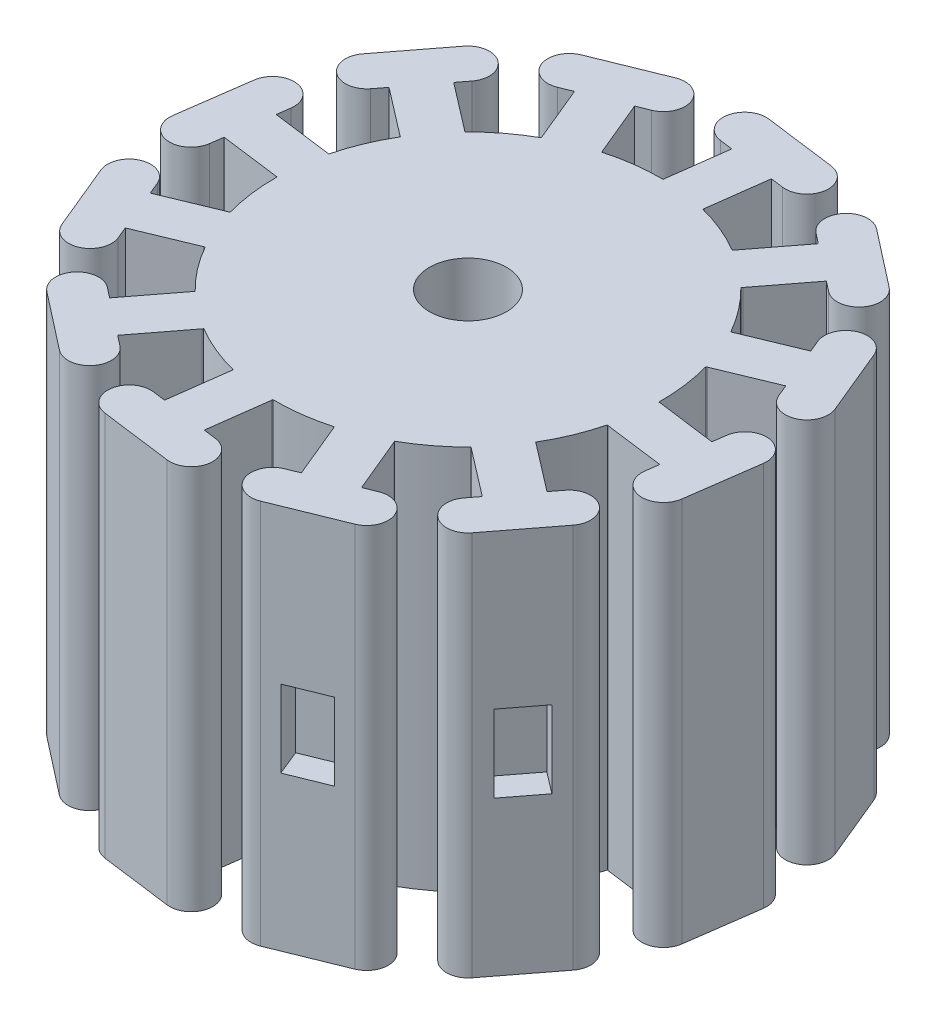
SolidWorks part; units mm, degrees
ref_plane "前视基准面" through (0, 0, 0) normal (0, 0, 1) x (1, 0, 0)
ref_plane "上视基准面" through (0, 0, 0) normal (0, 1, 0) x (1, 0, 0)
ref_plane "右视基准面" through (0, 0, 0) normal (1, 0, 0) x (0, 0, -1)
other "Configuration Table"
sketch "草图1" plane through (0, 0, 0) normal (0, 1, 0) x (1, 0, 0)
  line L0 (-16.5172, 2.1608) -> (-12.6081, 1.6494)
  line L25 (-16.1892, 4.5192) -> (-16.8451, -0.1975)
  line L26 (-19.002, 4.9103) -> (-19.6579, 0.1936)
  line L27 (-15.3899, -6.3747) -> (-11.7476, -4.866)
  line L28 (-16.3011, -4.1749) -> (-14.4787, -8.5745)
  line L29 (-18.9211, -5.2705) -> (-17.106, -9.6524)
  line L30 (-13.2156, 10.1407) -> (-10.0879, 7.7407)
  line L31 (-12.0083, -11.7607) -> (-8.2515, -14.6871)
  line L32 (-13.7535, -14.0011) -> (-9.9966, -16.9274)
  line L33 (-6.3873, 15.3847) -> (-4.8756, 11.7437)
  line L34 (-4.535, -16.2046) -> (0.1864, -16.8262)
  line L35 (-4.8962, -19.0214) -> (-0.1938, -19.6405)
  line L36 (2.1743, 16.5154) -> (1.6597, 12.6068)
  line L37 (4.1809, -16.2799) -> (8.5936, -14.4896)
  line L38 (5.2485, -18.9114) -> (9.6613, -17.1211)
  line L39 (10.1299, 13.2239) -> (7.7325, 10.0942)
  line L40 (11.7661, -12.0297) -> (14.6651, -8.2517)
  line L41 (14.0249, -13.7509) -> (16.9123, -9.988)
  line L42 (15.3899, 6.3747) -> (11.7476, 4.866)
  line L43 (16.1892, -4.5192) -> (16.8451, 0.1975)
  line L44 (19.002, -4.9103) -> (19.6579, -0.1936)
  line L45 (16.5172, -2.1608) -> (12.6081, -1.6494)
  line L46 (16.3011, 4.1749) -> (14.4787, 8.5745)
  line L47 (18.9211, 5.2705) -> (17.106, 9.6524)
  line L48 (13.2156, -10.1407) -> (10.0879, -7.7407)
  line L49 (12.0083, 11.7607) -> (8.2515, 14.6871)
  line L50 (13.7535, 14.0011) -> (9.9966, 16.9274)
  line L51 (6.3873, -15.3847) -> (4.8756, -11.7437)
  line L52 (4.535, 16.2046) -> (-0.1864, 16.8262)
  line L53 (4.9056, 19.0202) -> (0.1843, 19.6417)
  line L54 (-2.1743, -16.5154) -> (-1.6597, -12.6068)
  line L55 (-4.1809, 16.2799) -> (-8.5936, 14.4896)
  line L56 (-5.2485, 18.9114) -> (-9.6613, 17.1211)
  line L57 (-10.1299, -13.2239) -> (-7.7325, -10.0942)
  line L58 (-11.7661, 12.0297) -> (-14.6651, 8.2517)
  line L59 (-14.0249, 13.7509) -> (-16.9123, 9.988)
  line L60 (-6.3873, 15.3847) -> (-4.8756, 11.7437) construction
  line L61 (-4.9828, 15.9678) -> (-3.4711, 12.3268)
  line L62 (-7.7918, 14.8016) -> (-6.2801, 11.1606)
  line L63 (2.1743, 16.5154) -> (1.6597, 12.6068) construction
  line L64 (3.682, 16.3169) -> (3.1674, 12.4083)
  line L65 (0.6666, 16.7139) -> (0.152, 12.8053)
  line L66 (10.1299, 13.2239) -> (7.7325, 10.0942) construction
  line L67 (11.3371, 12.2991) -> (8.9397, 9.1695)
  line L68 (8.9227, 14.1487) -> (6.5253, 11.019)
  line L69 (15.3899, 6.3747) -> (11.7476, 4.866) construction
  line L70 (15.9719, 4.9697) -> (12.3296, 3.4611)
  line L71 (14.808, 7.7797) -> (11.1657, 6.271)
  line L72 (12.6081, -1.6494) -> (16.5172, -2.1608) construction
  line L73 (12.8054, -0.1415) -> (16.7145, -0.6529)
  line L74 (12.4109, -3.1573) -> (16.3199, -3.6687)
  line L75 (10.0879, -7.7407) -> (13.2156, -10.1407) construction
  line L76 (11.0137, -6.5343) -> (14.1414, -8.9342)
  line L77 (9.1622, -8.9472) -> (12.2899, -11.3472)
  line L78 (4.8756, -11.7437) -> (6.3873, -15.3847) construction
  line L79 (6.2801, -11.1606) -> (7.7918, -14.8016)
  line L80 (3.4711, -12.3268) -> (4.9828, -15.9678)
  line L81 (-1.6597, -12.6068) -> (-2.1743, -16.5154) construction
  line L82 (-0.152, -12.8053) -> (-0.6666, -16.7139)
  line L83 (-3.1674, -12.4083) -> (-3.682, -16.3169)
  line L84 (-7.7325, -10.0942) -> (-10.1299, -13.2239) construction
  line L85 (-6.5253, -11.019) -> (-8.9227, -14.1487)
  line L86 (-8.9397, -9.1695) -> (-11.3371, -12.2991)
  line L87 (-15.3899, -6.3747) -> (-11.7476, -4.866) construction
  line L88 (-15.9719, -4.9697) -> (-12.3296, -3.4611)
  line L89 (-14.808, -7.7797) -> (-11.1657, -6.271)
  line L90 (-16.5172, 2.1608) -> (-12.6081, 1.6494) construction
  line L91 (-16.3199, 3.6687) -> (-12.4109, 3.1573)
  line L92 (-16.7145, 0.6529) -> (-12.8054, 0.1415)
  line L93 (-13.2156, 10.1407) -> (-10.0879, 7.7407) construction
  line L94 (-12.2899, 11.3472) -> (-9.1622, 8.9472)
  line L95 (-14.1414, 8.9342) -> (-11.0137, 6.5343)
  circle A0 centre (0, 0) radius 2.54
  arc A1 (-16.0154, 7.7224) -> (-16.7805, 5.8774) centre (0, 0) ccw
  arc A2 (-7.7197, -16.0167) -> (-5.864, -16.7852) centre (0, 0) ccw
  circle A5 centre (0, 0) radius 12.7156
  arc A6 (-16.1892, 4.5192) -> (-19.002, 4.9103) centre (-17.5956, 4.7147) ccw
  arc A7 (-19.6579, 0.1936) -> (-16.8451, -0.1975) centre (-18.2515, -0.002) ccw
  arc A8 (-16.3011, -4.1749) -> (-18.9211, -5.2705) centre (-17.6093, -4.7271) ccw
  arc A9 (-17.106, -9.6524) -> (-14.4787, -8.5745) centre (-15.7942, -9.1091) ccw
  arc A10 (-12.0083, -11.7607) -> (-13.7535, -14.0011) centre (-12.8809, -12.8809) ccw
  arc A11 (-9.9966, -16.9274) -> (-8.2515, -14.6871) centre (-9.1241, -15.8073) ccw
  arc A12 (-4.535, -16.2046) -> (-4.8962, -19.0214) centre (-4.7108, -17.6136) ccw
  arc A13 (-0.1938, -19.6405) -> (0.1864, -16.8262) centre (-0.0084, -18.2327) ccw
  arc A14 (4.1809, -16.2799) -> (5.2485, -18.9114) centre (4.7147, -17.5956) ccw
  arc A15 (9.6613, -17.1211) -> (8.5936, -14.4896) centre (9.1275, -15.8053) ccw
  arc A16 (11.7661, -12.0297) -> (14.0249, -13.7509) centre (12.8984, -12.8865) ccw
  arc A17 (16.9123, -9.988) -> (14.6651, -8.2517) centre (15.7858, -9.1236) ccw
  arc A18 (16.1892, -4.5192) -> (19.002, -4.9103) centre (17.5956, -4.7147) ccw
  arc A19 (19.6579, -0.1936) -> (16.8451, 0.1975) centre (18.2515, 0.002) ccw
  arc A20 (16.3011, 4.1749) -> (18.9211, 5.2705) centre (17.6093, 4.7271) ccw
  arc A21 (17.106, 9.6524) -> (14.4787, 8.5745) centre (15.7942, 9.1091) ccw
  arc A22 (12.0083, 11.7607) -> (13.7535, 14.0011) centre (12.8809, 12.8809) ccw
  arc A23 (9.9966, 16.9274) -> (8.2515, 14.6871) centre (9.1241, 15.8073) ccw
  arc A24 (4.535, 16.2046) -> (4.9056, 19.0202) centre (4.7203, 17.6124) ccw
  arc A25 (0.1843, 19.6417) -> (-0.1864, 16.8262) centre (-0.001, 18.234) ccw
  arc A26 (-4.1809, 16.2799) -> (-5.2485, 18.9114) centre (-4.7147, 17.5956) ccw
  arc A27 (-9.6613, 17.1211) -> (-8.5936, 14.4896) centre (-9.1275, 15.8053) ccw
  arc A28 (-11.7661, 12.0297) -> (-14.0249, 13.7509) centre (-12.8984, 12.8865) ccw
  arc A29 (-16.9123, 9.988) -> (-14.6651, 8.2517) centre (-15.7858, 9.1236) ccw
  arc A32 (-17.7307, -1.3229) -> (-17.4684, -3.3142) centre (0, 0) ccw
  arc A35 (16.0154, -7.7224) -> (16.7805, -5.8774) centre (0, 0) ccw
  arc A36 (-14.6955, -10.0085) -> (-13.4802, -11.5936) centre (0, 0) ccw
  arc A37 (-4.9828, 15.9678) -> (-7.7918, 14.8016) centre (-6.3873, 15.3847) ccw
  arc A38 (-10.011, 14.6938) -> (-11.6044, 13.471) centre (0, 0) ccw
  arc A39 (-6.2801, 11.1606) -> (-3.4711, 12.3268) centre (-4.8756, 11.7437) ccw
  arc A40 (3.682, 16.3169) -> (0.6666, 16.7139) centre (2.1743, 16.5154) ccw
  arc A41 (0.152, 12.8053) -> (3.1674, 12.4083) centre (1.6597, 12.6068) ccw
  arc A42 (14.6955, 10.0085) -> (-3.3003, 17.471) centre (0, 0) ccw
  arc A43 (17.7307, 1.3229) -> (17.4684, 3.3142) centre (0, 0) ccw
  arc A44 (10.011, -14.6938) -> (11.6044, -13.471) centre (0, 0) ccw
  arc A45 (1.3199, -17.7309) -> (3.3003, -17.471) centre (0, 0) ccw
  arc A46 (11.3371, 12.2991) -> (8.9227, 14.1487) centre (10.1299, 13.2239) ccw
  arc A47 (6.5253, 11.019) -> (8.9397, 9.1695) centre (7.7325, 10.0942) ccw
  arc A48 (15.9719, 4.9697) -> (14.808, 7.7797) centre (15.3899, 6.3747) ccw
  arc A49 (11.1657, 6.271) -> (12.3296, 3.4611) centre (11.7476, 4.866) ccw
  arc A50 (12.8054, -0.1415) -> (12.4109, -3.1573) centre (12.6081, -1.6494) ccw
  arc A51 (16.3199, -3.6687) -> (16.7145, -0.6529) centre (16.5172, -2.1608) ccw
  arc A52 (11.0137, -6.5343) -> (9.1622, -8.9472) centre (10.0879, -7.7407) ccw
  arc A53 (12.2899, -11.3472) -> (14.1414, -8.9342) centre (13.2156, -10.1407) ccw
  arc A54 (6.2801, -11.1606) -> (3.4711, -12.3268) centre (4.8756, -11.7437) ccw
  arc A55 (4.9828, -15.9678) -> (7.7918, -14.8016) centre (6.3873, -15.3847) ccw
  arc A56 (-0.152, -12.8053) -> (-3.1674, -12.4083) centre (-1.6597, -12.6068) ccw
  arc A57 (-3.682, -16.3169) -> (-0.6666, -16.7139) centre (-2.1743, -16.5154) ccw
  arc A58 (-6.5253, -11.019) -> (-8.9397, -9.1695) centre (-7.7325, -10.0942) ccw
  arc A59 (-11.3371, -12.2991) -> (-8.9227, -14.1487) centre (-10.1299, -13.2239) ccw
  arc A60 (-15.9719, -4.9697) -> (-14.808, -7.7797) centre (-15.3899, -6.3747) ccw
  arc A61 (-11.1657, -6.271) -> (-12.3296, -3.4611) centre (-11.7476, -4.866) ccw
  arc A62 (-16.3199, 3.6687) -> (-16.7145, 0.6529) centre (-16.5172, 2.1608) ccw
  arc A63 (-12.8054, 0.1415) -> (-12.4109, 3.1573) centre (-12.6081, 1.6494) ccw
  arc A64 (-12.2899, 11.3472) -> (-14.1414, 8.9342) centre (-13.2156, 10.1407) ccw
  arc A65 (-11.0137, 6.5343) -> (-9.1622, 8.9472) centre (-10.0879, 7.7407) ccw
  point P4 (-17.9236, 2.3564)
  point P37 (-16.7179, -6.9248)
  point P42 (-11.0025, -14.3441)
  point P47 (-2.3619, -17.9405)
  point P52 (6.9211, -16.7005)
  point P57 (14.356, -11.0157)
  point P62 (17.9236, -2.3564)
  point P67 (16.7179, 6.9248)
  point P72 (11.0025, 14.3441)
  point P77 (2.3619, 17.9405)
  point P82 (-6.9211, 16.7005)
  point P88 (-14.356, 11.0157)
  point P127 (-5.6314, 13.5642)
  point P135 (1.917, 14.5611)
  point P140 (8.9312, 11.6591)
  point P148 (13.5688, 5.6204)
  point P153 (14.5627, -1.9051)
  point P158 (11.6518, -8.9407)
  point P163 (5.6314, -13.5642)
  point P168 (-1.917, -14.5611)
  point P173 (-8.9312, -11.6591)
  point P178 (-13.5688, -5.6204)
  point P183 (-14.5627, 1.9051)
  point P188 (-11.6518, 8.9407)
  dimension "D1" = 5.08
  dimension "D2" = 35.56
extrude "凸台-拉伸2" add sketch "草图1" along normal blind 25.4 contours A65 A5 A63 A61 A58 A56 A54 A52 A50 A49 A47 A41 A39 A0 | A5 A58 | A5 A56 | A5 A54 | A5 A52 | A5 A50 | A5 A49 | A5 A47 | A5 A41 | A5 A39 | A5 A65 | A5 A63 | A5 A61 | L89 A61 A5 L27 L28 | A5 A61 L88 L28 L27 | A5 A58 L86 L31 L57 | L31 A59 L85 A58 A5 L57 | A5 A56 L83 L34 L54 | L82 A56 A5 L54 L34 | A5 A54 L80 L37 L51 | L37 A55 L79 A54 A5 L51 | A5 A52 L77 L40 L48 | L76 A52 A5 L48 L40 | A5 A50 L74 L43 L45 | L43 A51 L73 A50 A5 L45 | A5 A49 L70 L46 L42 | L71 A49 A5 L42 L46 | A5 A47 L67 L49 L39 | L68 A47 A5 L39 L49 A46 | A5 A41 L64 L52 L36 | L65 A41 A5 L36 L52 | A5 A39 L61 L55 L33 | L62 A39 A5 L33 L55 A37 | A5 A65 L94 L58 L30 | L95 A65 A5 L30 L58 | A5 A63 L91 L25 L0 | L92 A63 A5 L0 L25 A62 | L91 A62 L25 | A62 L91 L25 A6 L26 A7 | A60 L28 A8 L29 A9 | L28 A60 | A59 L86 L31 A10 L32 A11 | L86 A59 L31 | A57 L34 A12 L35 A13 | L34 A57 | A55 L80 L37 A14 L38 A15 | L80 A55 L37 | L40 A53 | A53 L40 A16 L41 A17 | L74 A51 L43 | A51 L74 L43 A18 L44 A19 | L46 A48 | A48 L46 A20 L47 A21 | L67 A46 A42 L49 | A46 L67 L49 A22 A42 | A46 A42 A22 L50 A23 | A42 A46 | A46 A42 A23 L49 | A42 A24 L53 A25 A40 | A40 A42 L52 | L58 A64 | A64 L58 A28 L59 A29 | L61 A37 L55 | A37 L61 L55 A26 L56 A27 | A42 A40 | A40 A42 A25 L52 | A24 A42 A40 L52
sketch "草图2" plane through (11.9814, 0, -15.3814) normal (0.6145, 0, -0.7889) x (-0.7889, 0, -0.6145)
  line L0 (-2.2462, 25.4) -> (-2.2462, 0) construction
  line L1 (-1.2302, 15.24) -> (1.4999, 15.24)
  line L2 (-1.2302, 15.24) -> (-1.2302, 10.16)
  line L3 (-1.2302, 10.16) -> (1.4999, 10.16)
  line L4 (1.4999, 15.24) -> (1.4999, 10.16)
  line L5 (2.5159, 25.4) -> (2.5159, 0) construction
  line L6 (-2.2462, 25.4) -> (2.5159, 25.4) construction
  line L7 (-2.2462, 0) -> (2.5159, 0) construction
  dimension "D1" = 1.016
  dimension "D2" = 1.016
  dimension "D3" = 10.16
  dimension "D4" = 10.16
extrude "切除-拉伸1" cut sketch "草图2" against normal blind 1.778
sketch "草图3" plane through (2.545, 0, -19.331) normal (0.1305, 0, -0.9914) x (-0.9914, 0, -0.1305)
  line L0 (-1.365, 15.24) -> (1.365, 15.24)
  line L1 (-1.365, 15.24) -> (-1.365, 10.0701)
  line L2 (-1.365, 10.0701) -> (1.365, 10.0701)
  line L3 (1.365, 15.24) -> (1.365, 10.0701)
  line L4 (-2.381, 25.4) -> (-2.381, 0) construction
  line L5 (-2.381, 25.4) -> (2.381, 25.4) construction
  line L6 (2.381, 25.4) -> (2.381, 0) construction
  dimension "D1" = 1.016
  dimension "D2" = 10.16
  dimension "D3" = 1.016
extrude "切除-拉伸2" cut sketch "草图3" against normal blind 1.778
sketch "草图4" plane through (15.4686, 0, 11.8695) normal (0.7934, 0, 0.6088) x (0.6088, 0, -0.7934)
  line L0 (-1.3555, 15.24) -> (1.3746, 15.24)
  line L1 (-1.3555, 15.24) -> (-1.3555, 10.16)
  line L2 (-1.3555, 10.16) -> (1.3746, 10.16)
  line L3 (1.3746, 15.24) -> (1.3746, 10.16)
  line L4 (-2.3715, 25.4) -> (2.3715, 25.4) construction
  line L5 (-2.3715, 25.4) -> (-2.3715, 0) construction
  dimension "D1" = 10.16
  dimension "D2" = 1.016
extrude "切除-拉伸3" cut sketch "草图4" against normal blind 1.778
sketch "草图5" plane through (7.33, 0, 18.0669) normal (0.3759, 0, 0.9266) x (0.9266, 0, -0.3759)
  line L0 (-1.2302, 15.24) -> (1.4999, 15.24)
  line L1 (-1.2302, 15.24) -> (-1.2302, 10.16)
  line L2 (-1.2302, 10.16) -> (1.4999, 10.16)
  line L3 (1.4999, 15.24) -> (1.4999, 10.16)
  line L4 (-2.2462, 25.4) -> (2.5159, 25.4) construction
  line L5 (-2.2462, 25.4) -> (-2.2462, 0) construction
  dimension "D1" = 10.16
  dimension "D2" = 1.016
extrude "切除-拉伸4" cut sketch "草图5" against normal blind 1.778
sketch "草图6" plane through (-19.3114, 0, -2.6855) normal (-0.9905, 0, -0.1377) x (-0.1377, 0, 0.9905)
  line L0 (-1.2302, 15.24) -> (1.4999, 15.24)
  line L1 (-1.2302, 15.24) -> (-1.2302, 10.16)
  line L2 (-1.2302, 10.16) -> (1.4999, 10.16)
  line L3 (1.4999, 15.24) -> (1.4999, 10.16)
  line L4 (-2.2462, 25.4) -> (2.5159, 25.4) construction
  line L5 (-2.2462, 25.4) -> (-2.2462, 0) construction
  dimension "D1" = 10.16
  dimension "D2" = 1.016
extrude "切除-拉伸5" cut sketch "草图6" against normal blind 1.778
sketch "草图7" plane through (-15.4686, 0, -11.8695) normal (-0.7934, 0, -0.6088) x (-0.6088, 0, 0.7934)
  line L0 (-1.3555, 15.24) -> (1.3746, 15.24)
  line L1 (-1.3555, 15.24) -> (-1.3555, 10.16)
  line L2 (-1.3555, 10.16) -> (1.3746, 10.16)
  line L3 (1.3746, 15.24) -> (1.3746, 10.16)
  line L4 (-2.3715, 25.4) -> (2.3715, 25.4) construction
  line L5 (-2.3715, 25.4) -> (-2.3715, 0) construction
  dimension "D1" = 10.16
  dimension "D2" = 1.016
extrude "切除-拉伸6" cut sketch "草图7" against normal blind 1.778
